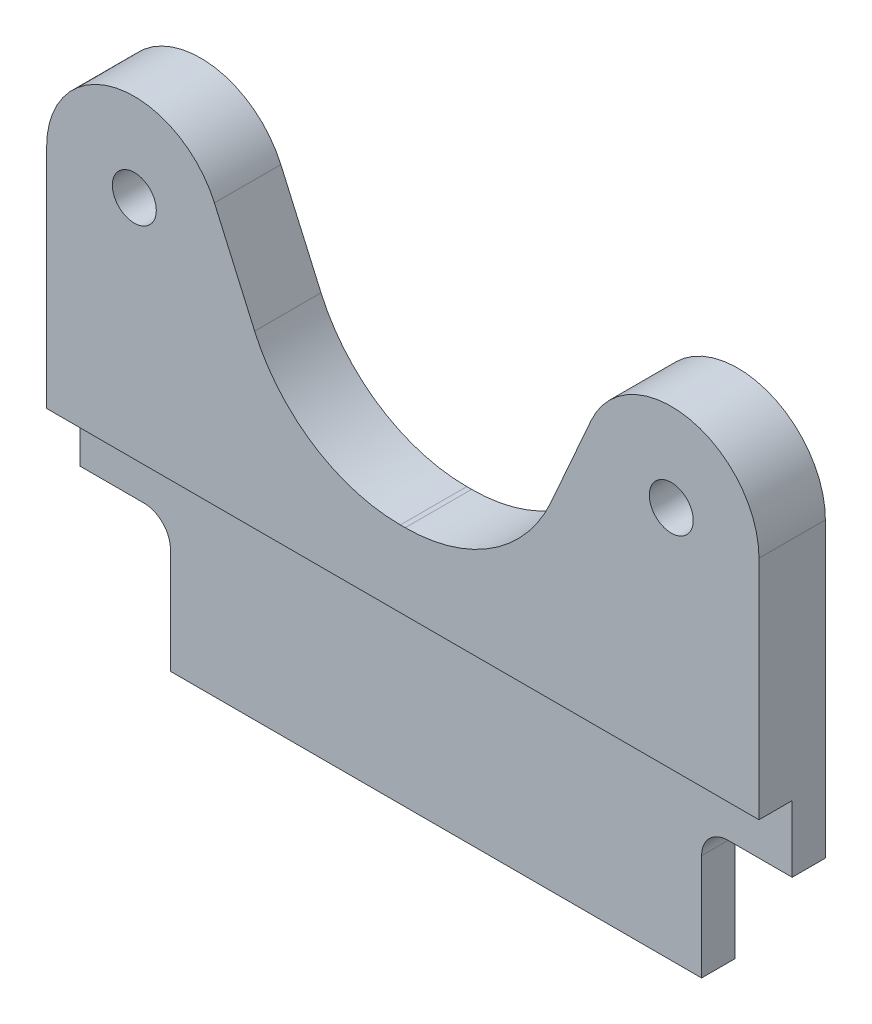
SolidWorks part; units mm, degrees
ref_plane "Plan de face" through (0, 0, 0) normal (0, 0, 1) x (1, 0, 0)
ref_plane "Plan de dessus" through (0, 0, 0) normal (0, 1, 0) x (1, 0, 0)
ref_plane "Plan de droite" through (0, 0, 0) normal (1, 0, 0) x (0, 0, -1)
sketch "Esquisse2" plane through (0, 0, 0) normal (0, 0, 1) x (1, 0, 0)
  line L5 (25.4, 0) -> (33.653, 25.4)
  line L7 (10.16, 13.597) -> (-10.16, 13.597)
  line L10 (-25.4, 0) -> (-33.653, 25.4)
  line L12 (-25.4, 0) -> (25.4, 0) construction
  line L13 (-10.16, 13.597) -> (-18.0139, 31.377)
  line L14 (10.16, 13.597) -> (18.0139, 31.377)
  line L17 (-25.4, 0) -> (-25.4, -12.7)
  line L18 (-25.4, -12.7) -> (25.4, -12.7)
  line L19 (25.4, 0) -> (25.4, -12.7)
  arc A5 (-33.653, 25.4) -> (-18.0139, 31.377) centre (-25.6812, 27.9902) cw
  arc A6 (33.653, 25.4) -> (18.0139, 31.377) centre (25.6812, 27.9902) ccw
  point P4 (0, 0)
  point P6 (0, 0)
  point P13 (0, 13.597)
  dimension "D3" = 108
  dimension "D8" = 8.382
  dimension "D2" = 20.32
  dimension "D4" = 108
  dimension "D5" = 50.8
  dimension "D6" = 17.78
  dimension "D7" = 113.832
  dimension "D9" = 25.4
  dimension "D10" = 113.832
  dimension "D11" = 12.7
extrude "Boss.-Extru.1" add sketch "Esquisse2" along normal mid plane 6.35
sketch "Esquisse3" plane through (0, 0, 3.175) normal (0, 0, 1) x (1, 0, 0)
  line L0 (-33.653, 25.4) -> (-25.4, 0) construction
  circle A0 centre (-25.6739, 27.9676) radius 2.1
  arc A1 (-18.0139, 31.377) -> (-33.653, 25.4) centre (-25.6812, 27.9902) ccw construction
  dimension "D1" = 4.2
  dimension "D2" = 8.382
  dimension "D3" = 0.0238
extrude "Enlèv. mat.-Extru.1" cut sketch "Esquisse3" against normal through all
mirror "Symétrie1" about plane through (0, 0, 0) normal (1, 0, 0) of "Enlèv. mat.-Extru.1"
sketch "Esquisse4" plane through (0, 0, 3.175) normal (0, 0, 1) x (1, 0, 0)
  line L0 (-27.4548, 6.3242) -> (27.4548, 6.3242)
  line L6 (25.4, -12.7) -> (25.4, 0)
  line L7 (25.4, 0) -> (33.653, 25.4)
  line L8 (18.0139, 31.377) -> (10.16, 13.597)
  line L9 (10.16, 13.597) -> (-10.16, 13.597)
  line L10 (-10.16, 13.597) -> (-18.0139, 31.377)
  line L14 (18.0139, 31.377) -> (10.16, 13.597)
  line L15 (10.16, 13.597) -> (-10.16, 13.597)
  line L16 (-10.16, 13.597) -> (-18.0139, 31.377)
  line L21 (25.4, -12.7) -> (25.4, 0)
  line L22 (-25.4, 0) -> (-25.4, -12.7)
  line L23 (-25.4, 0) -> (-25.4, -12.7)
  line L24 (-25.4, -12.7) -> (25.4, -12.7)
  line L25 (-25.4, -12.7) -> (25.4, -12.7)
  line L26 (25.4, 0) -> (33.653, 25.4)
  line L27 (-33.653, 25.4) -> (-25.4, 0)
  line L28 (-33.653, 25.4) -> (-25.4, 0)
  arc A2 (33.653, 25.4) -> (18.0139, 31.377) centre (25.6812, 27.9902) ccw
  arc A3 (-18.0139, 31.377) -> (-33.653, 25.4) centre (-25.6812, 27.9902) ccw
  arc A4 (33.653, 25.4) -> (18.0139, 31.377) centre (25.6812, 27.9902) ccw
  arc A5 (-18.0139, 31.377) -> (-33.653, 25.4) centre (-25.6812, 27.9902) ccw
  dimension "D1" = 0
extrude "Enlèv. mat.-Extru.2" cut sketch "Esquisse4" against normal blind 3.175
fillet "Congé1" radius 15.24 2 edges at (10.16, 13.597, 0) (-10.16, 13.597, 0)
fillet "Congé2" radius 15.24 2 edges at (25.4, 0, -1.5875) (-25.4, 0, -1.5875)
sketch "Esquisse8" plane through (0, 0, 0) normal (0, 0, 1) x (1, 0, 0)
  line L2 (-27.4548, 6.3242) -> (-26.1459, 2.2956) construction
  line L3 (-33.653, 25.4) -> (-27.4548, 6.3242) construction
  line L4 (-27.4548, 6.3242) -> (-26.1459, 2.2956)
  line L5 (-33.653, 25.4) -> (-27.4548, 6.3242)
  line L6 (-34.0632, 27.9902) -> (-34.0632, -0.0297)
  line L7 (-34.0632, -0.0297) -> (-25.5876, -0.0297)
  arc A0 (-25.4, -2.4138) -> (-26.1459, 2.2956) centre (-40.64, -2.4138) ccw construction
  arc A3 (-25.5876, -0.0297) -> (-26.1459, 2.2956) centre (-40.64, -2.4138) ccw
  arc A8 (-18.0139, 31.377) -> (-33.653, 25.4) centre (-25.6812, 27.9902) ccw construction
  arc A9 (-34.0632, 27.9902) -> (-33.653, 25.4) centre (-25.6812, 27.9902) ccw
  dimension "D1" = 8.4756
extrude "Boss.-Extru.3" add sketch "Esquisse8" along normal up to surface and the other way up to surface up to face at (-23.5739, 27.9676, 3.175) other way up to face at (23.5739, 27.9676, -3.175)
mirror "Symétrie2" about plane through (0, 0, 0) normal (1, 0, 0) of "Boss.-Extru.3"
sketch "Esquisse9" plane through (0, 0, 3.175) normal (0, 0, 1) x (1, 0, 0)
  line L3 (-27.4548, 6.3242) -> (-26.1459, 2.2956) construction
  line L6 (-27.4548, 6.3242) -> (-26.1459, 2.2956)
  line L11 (-27.4548, 6.3242) -> (-34.0632, 6.3242)
  line L12 (-34.0632, -0.0297) -> (-34.0632, 27.9902) construction
  line L13 (-34.0632, 6.3242) -> (-34.0632, -0.0297)
  line L14 (-34.0632, -0.0297) -> (-25.5876, -0.0297)
  arc A0 (-25.5876, -0.0297) -> (-26.1459, 2.2956) centre (-40.64, -2.4138) ccw construction
  arc A1 (-25.5876, -0.0297) -> (-26.1459, 2.2956) centre (-40.64, -2.4138) ccw
extrude "Enlèv. mat.-Extru.3" cut sketch "Esquisse9" against normal up to surface (3.175 mm away) up to face at (0, -1.3018, 0)
mirror "Symétrie3" about plane through (0, 0, 0) normal (1, 0, 0) of "Enlèv. mat.-Extru.3"
fillet "Congé3" radius 2.54 2 edges at (25.5876, -0.0297, -1.5875) (-25.5876, -0.0297, -1.5875)
